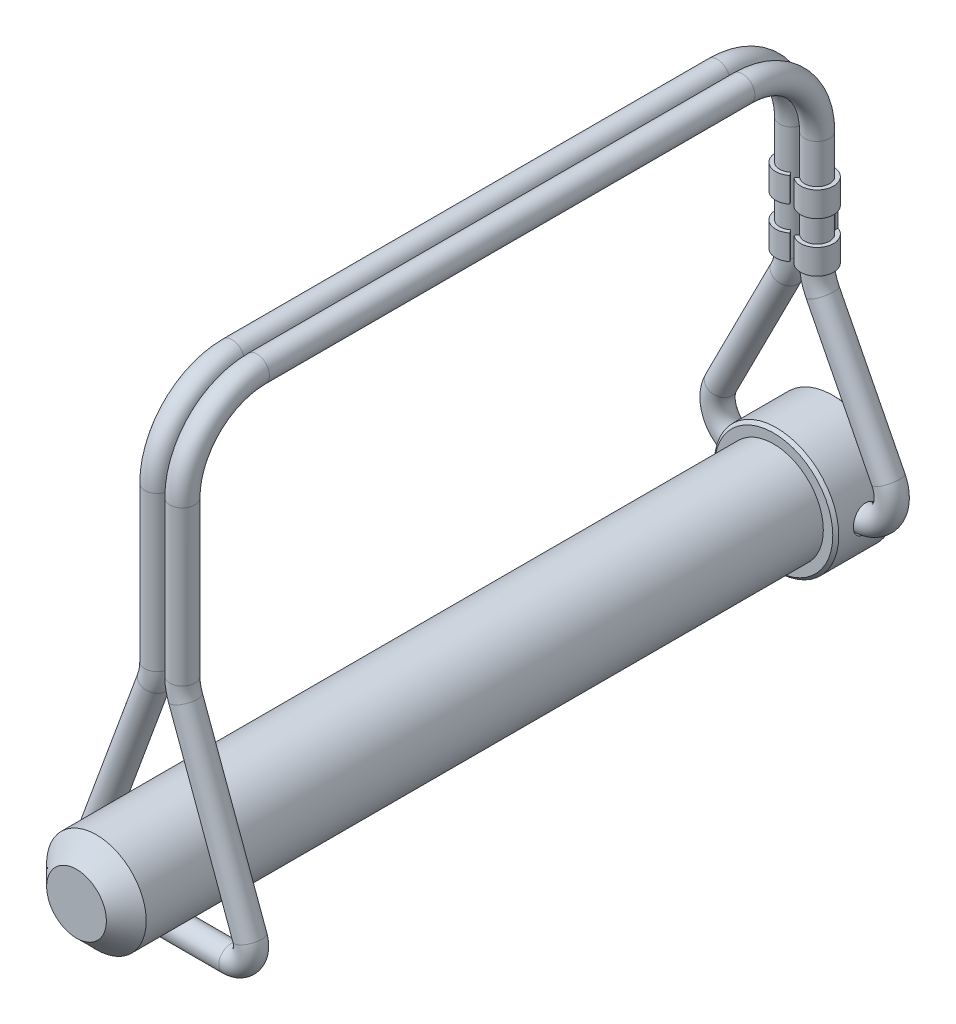
SolidWorks part; units mm, degrees
material "Low Carbon Steel"
ref_plane "Front" through (0, 0, 0) normal (0, 0, 1) x (1, 0, 0)
ref_plane "Top" through (0, 0, 0) normal (0, 1, 0) x (1, 0, 0)
ref_plane "Right" through (0, 0, 0) normal (1, 0, 0) x (0, 0, -1)
sketch "Sketch1" plane through (0, 0, 0) normal (1, 0, 0) x (0, 0, -1)
  line L0 (-48.4187, 0) -> (48.4187, 0)
  line L1 (48.4187, 0) -> (48.4187, 7.5565)
  line L2 (48.0377, 7.9375) -> (40.8622, 7.9375)
  line L3 (40.4812, 7.5565) -> (40.4812, 6.35)
  line L4 (40.4812, 6.35) -> (-45.8787, 6.35)
  line L5 (-48.4187, 3.81) -> (-48.4187, 0)
  line L6 (0, 0) -> (0, 6.35) construction
  line L7 (0, 0) -> (0, -6.35) construction
  line L8 (44.45, 7.9375) -> (44.45, 0) construction
  line L9 (44.45, 0) -> (44.45, -7.9375) construction
  line L10 (-45.8787, 6.35) -> (-48.4187, 3.81)
  line L11 (40.8622, 7.9375) -> (40.4812, 7.5565)
  line L12 (48.4187, 7.5565) -> (48.0377, 7.9375)
  line L13 (-48.4187, 3.81) -> (-48.4187, 6.35) construction
  line L14 (-48.4187, 6.35) -> (-45.8787, 6.35) construction
  point P4 (48.4187, 7.9375)
  point P5 (40.4812, 7.9375)
  point P7 (-48.4187, 6.35)
  dimension "D1" = 2.54
revolve "Revolve1" add sketch "Sketch1" angle 360 mid plane about L0
sketch "Sketch2" plane through (0, 0, 0) normal (1, 0, 0) x (0, 0, -1)
  line L0 (40.4812, 0) -> (48.4187, 0) construction
  line L1 (40.4812, 6.35) -> (40.4812, -6.35) construction
  line L2 (48.4187, -7.5565) -> (48.4187, 7.5565) construction
  line L3 (44.45, 1.5875) -> (44.45, -1.5875) construction
  circle A0 centre (44.45, 0) radius 1.7145
  circle A1 centre (44.45, 0) radius 1.5875 construction
  dimension "WireDiameter" = 3.175
extrude "Cut-Extrude1" cut sketch "Sketch2" against normal through all and the other way through all
ref_plane "Plane1" through (1.5938, 0, 0) normal (1, 0, 0) x (0, 0, -1)
ref_plane "Plane2" through (-1.5938, 0, 0) normal (1, 0, 0) x (0, 0, -1)
sketch "Sketch3" plane through (1.5938, 0, 0) normal (1, 0, 0) x (0, 0, -1)
  line L0 (44.45, 0) -> (44.45, 25.7969) construction
  line L1 (44.45, 25.7969) -> (44.45, 39.6875)
  line L2 (34.925, 49.2125) -> (-26.9875, 49.2125)
  line L3 (-36.5125, 39.6875) -> (-36.5125, 20.6375)
  line L5 (44.45, 0) -> (-36.5125, 0) construction
  line L6 (-36.5125, 0) -> (-36.5125, 20.6375) construction
  line L7 (0, 47.625) -> (0, 50.8) construction
  line L8 (44.45, 1.5875) -> (44.45, -1.5875) construction
  line L9 (0, 49.2125) -> (44.45, 0) construction
  line L10 (40.4812, 6.35) -> (-45.8787, 6.35) construction
  line L11 (42.8625, 25.7969) -> (46.0375, 25.7969) construction
  line L12 (-38.1, 20.6375) -> (-34.925, 20.6375) construction
  arc A0 (-26.9875, 49.2125) -> (-36.5125, 39.6875) centre (-26.9875, 39.6875) ccw
  arc A1 (44.45, 39.6875) -> (34.925, 49.2125) centre (34.925, 39.6875) ccw
  point P12 (-36.5125, 49.2125)
  point P15 (44.45, 49.2125)
  dimension "D5" = 9.525
  dimension "D1" = 25.7969
  dimension "D3" = 20.6375
sketch "Sketch4" plane through (-1.5938, 0, 0) normal (1, 0, 0) x (0, 0, -1)
  line L0 (44.45, 25.7969) -> (44.45, 39.6875) construction
  line L1 (34.925, 49.2125) -> (-26.9875, 49.2125) construction
  line L2 (-36.5125, 39.6875) -> (-36.5125, 20.6375) construction
  line L3 (44.45, 25.7969) -> (44.45, 39.6875)
  line L4 (34.925, 49.2125) -> (-26.9875, 49.2125)
  line L5 (-36.5125, 39.6875) -> (-36.5125, 20.6375)
  arc A0 (44.45, 39.6875) -> (34.925, 49.2125) centre (34.925, 39.6875) ccw construction
  arc A1 (-26.9875, 49.2125) -> (-36.5125, 39.6875) centre (-26.9875, 39.6875) ccw construction
  arc A2 (44.45, 39.6875) -> (34.925, 49.2125) centre (34.925, 39.6875) ccw
  arc A3 (-26.9875, 49.2125) -> (-36.5125, 39.6875) centre (-26.9875, 39.6875) ccw
ref_plane "Plane3" through (0, 0, -44.45) normal (0, 0, -1) x (-1, 0, 0)
sketch "Sketch5" plane through (0, 0, -44.45) normal (0, 0, -1) x (-1, 0, 0)
  line L0 (-7.1437, 0) -> (7.1437, 0)
  line L1 (10.6815, 5.7675) -> (2.2835, 22.2838)
  line L2 (1.5938, 39.6875) -> (1.5938, 20.6375) construction
  line L3 (-10.6815, 5.7675) -> (-2.2835, 22.2838)
  line L4 (-1.5938, 0) -> (-1.5938, 25.7969) construction
  line L5 (-1.5938, 25.7969) -> (-1.5938, 25.1619)
  line L6 (1.5938, 25.7969) -> (1.5938, 25.1619)
  arc A0 (-10.6815, 5.7675) -> (-7.1437, 0) centre (-7.1437, 3.9688) ccw
  arc A1 (7.1437, 0) -> (10.6815, 5.7675) centre (7.1437, 3.9688) ccw
  arc A2 (1.5938, 25.1619) -> (2.2835, 22.2838) centre (7.9438, 25.1619) ccw
  arc A3 (-2.2835, 22.2838) -> (-1.5938, 25.1619) centre (-7.9439, 25.1619) ccw
  point P20 (1.5939, 23.6402)
  point P23 (-1.5938, 23.6402)
  dimension "D1" = 7.9375
  dimension "D2" = 6.35
  dimension "D3" = 0.635
  dimension "D4" = 14.2875
ref_plane "Plane4" through (0, 0, 36.5125) normal (0, 0, -1) x (-1, 0, 0)
sketch "Sketch6" plane through (0, 0, 36.5125) normal (0, 0, -1) x (-1, 0, 0)
  line L0 (1.5939, 20.6375) -> (1.5939, 20.0025)
  line L1 (-1.5938, 20.6375) -> (-1.5938, 20.0025)
  line L2 (1.9829, 17.814) -> (10.2068, -4.5856)
  line L3 (7.8224, -8.001) -> (-7.8224, -8.001)
  line L4 (-10.2068, -4.5856) -> (-1.9829, 17.814)
  line L5 (0, -6.35) -> (0, -8.001) construction
  line L6 (0, -8.001) -> (0, -9.652) construction
  line L7 (-7.5108, 2.7575) -> (-5.9609, 2.1885) construction
  line L8 (-7.5108, 2.7575) -> (-9.0606, 3.3266) construction
  arc A1 (-1.5938, 20.0025) -> (-1.9829, 17.814) centre (-7.9438, 20.0025) cw
  arc A2 (1.5939, 20.0025) -> (1.9829, 17.814) centre (7.9439, 20.0025) ccw
  circle A3 centre (0, 0) radius 6.35 construction
  circle A4 centre (0, 0) radius 6.35 construction
  arc A5 (-7.8224, -8.001) -> (-10.2068, -4.5856) centre (-7.8224, -5.461) cw
  arc A6 (10.2068, -4.5856) -> (7.8224, -8.001) centre (7.8224, -5.461) cw
  dimension "D1" = 6.35
  dimension "D4" = 2.54
  dimension "D2" = 0.635
  dimension "D3" = 3.302
curve "CompCurve1"
sketch "Sketch7" plane through (0, 0, 0) normal (1, 0, 0) x (0, 0, -1)
  circle A0 centre (44.45, 0) radius 1.5875
sweep "Sweep1" add profiles "Sketch7" path "CompCurve1"
ref_plane "Plane5" through (0, 25.1619, 0) normal (0, 1, 0) x (1, 0, 0)
sketch "Sketch8" plane through (0, 25.1619, 0) normal (0, 1, 0) x (1, 0, 0)
  line L0 (1.5938, 46.0375) -> (-1.5938, 46.0375)
  line L1 (-1.5938, 46.5455) -> (1.5938, 46.5455)
  line L2 (0.5788, 43.2294) -> (0.254, 42.8388)
  line L3 (-0.5788, 43.2294) -> (-0.254, 42.8388)
  line L4 (-0.254, 42.8388) -> (0.254, 42.8388) construction
  circle A0 centre (1.5938, 44.45) radius 1.5875 construction
  arc A1 (0.5788, 43.2294) -> (1.5938, 46.0375) centre (1.5938, 44.45) ccw
  circle A2 centre (-1.5938, 44.45) radius 1.5875 construction
  arc A3 (-1.5938, 46.0375) -> (-0.5788, 43.2294) centre (-1.5938, 44.45) ccw
  arc A4 (-1.5938, 46.5455) -> (-0.254, 42.8388) centre (-1.5938, 44.45) ccw
  arc A6 (0.254, 42.8388) -> (1.5938, 46.5455) centre (1.5938, 44.45) ccw
  dimension "D1" = 0.508
extrude "Boss-Extrude1" add sketch "Sketch8" along normal blind 9.525 separate body
sketch "Sketch9" plane through (0, 0, 0) normal (1, 0, 0) x (0, 0, -1)
  line L0 (46.0375, 34.6869) -> (46.0375, 31.5119) construction
  line L1 (46.0375, 31.5119) -> (46.0375, 28.3369) construction
  line L2 (46.0375, 28.3369) -> (46.0375, 25.1619) construction
  line L3 (46.0375, 31.5119) -> (0, 31.5119)
  line L4 (0, 31.5119) -> (0, 28.3369)
  line L5 (0, 28.3369) -> (46.0375, 28.3369)
  line L6 (46.0375, 31.5119) -> (46.0375, 28.3369)
extrude "Cut-Extrude4" cut sketch "Sketch9" against normal through all and the other way through all
sketch "Sketch10" plane through (0, 0, -46.5455) normal (0, 0, -1) x (-1, 0, 0)
  line L1 (-2.9617, 28.3369) -> (-2.2778, 28.3369)
  line L2 (-2.9617, 28.3369) -> (-2.9617, 31.5119)
  line L3 (-2.9617, 31.5119) -> (-2.2778, 31.5119)
  line L4 (-2.2778, 28.3369) -> (-2.2778, 31.5119)
  line L5 (-2.9617, 31.5119) -> (-2.9617, 28.3369) construction
  line L6 (-3.6894, 31.5119) -> (-0.254, 31.5119) construction
  line L7 (0, 25.1619) -> (0, 34.6869) construction
  line L8 (-1.5939, 25.1619) -> (1.5938, 25.1619) construction
  line L9 (-1.5939, 34.6869) -> (1.5938, 34.6869) construction
  line L10 (2.2778, 28.3369) -> (2.2778, 31.5119)
  line L11 (2.9617, 31.5119) -> (2.2778, 31.5119)
  line L12 (2.9617, 28.3369) -> (2.9617, 31.5119)
  line L13 (2.9617, 28.3369) -> (2.2778, 28.3369)
  line L14 (-2.2778, 31.5119) -> (-1.5939, 31.5119) construction
  line L15 (-1.5939, 34.6869) -> (-1.5939, 25.1619) construction
extrude "Cut-Extrude5" cut sketch "Sketch10" against normal through all
other "Freeze***"
equation "\"D1@Plane2\" = \"D1@Plane1\""
equation "\"D1@Sketch1\"=\"PinDiameter@Sketch1\"*.2"
equation "\"D1@Sketch3\"=\"RetainerClearanceHeight@Sketch3\"*.625"
equation "\"D3@Sketch3\"=\"RetainerClearanceHeight@Sketch3\"*.5"
equation "\"D4@Sketch5\"=\"HeadDiameter@Sketch1\"*.9"
equation "\"D3@Sketch6\"=\"WireDiameter@Sketch2\"+\"D1@Sketch2\""
